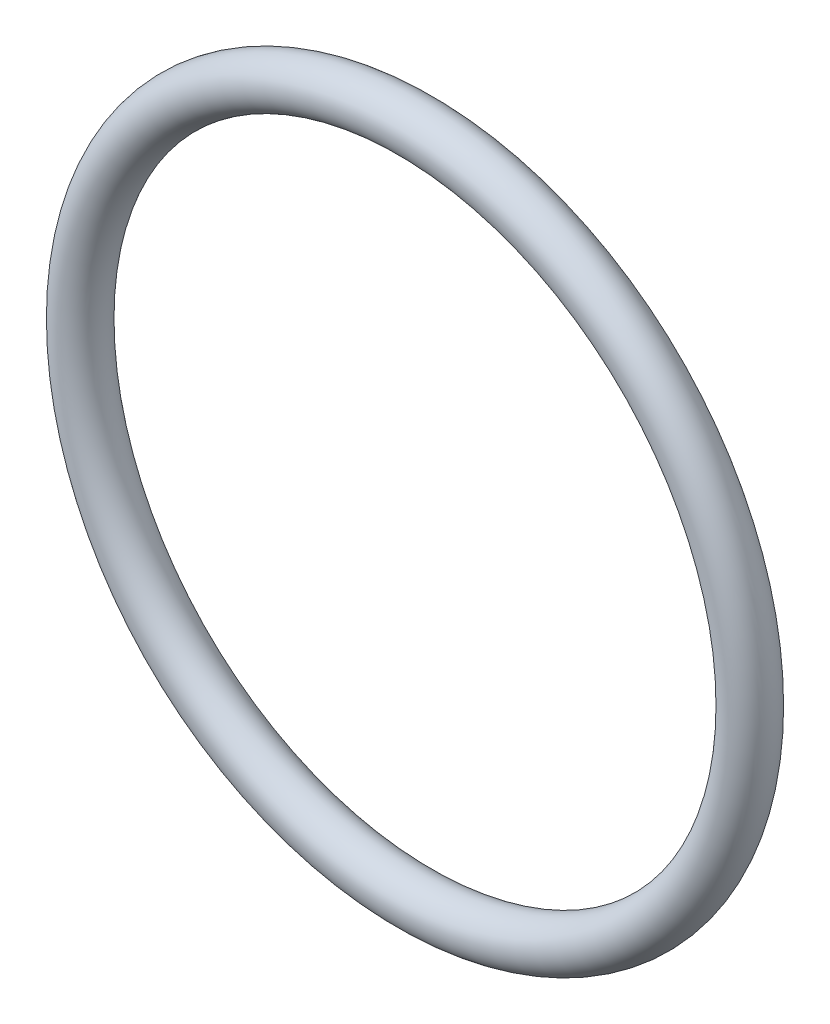
SolidWorks part; units mm, degrees
ref_plane "Front" through (0, 0, 0) normal (0, 0, 1) x (1, 0, 0)
ref_plane "Top" through (0, 0, 0) normal (0, 1, 0) x (1, 0, 0)
ref_plane "Right" through (0, 0, 0) normal (1, 0, 0) x (0, 0, -1)
sketch "Sketch1" plane through (0, 0, 0) normal (1, 0, 0) x (0, -1, 0)
  line L0 (0, -1.5) -> (0, 1.5) construction
  line L2 (-41.8, 0) -> (41.8, 0) construction
  line L3 (-19.5, 0) -> (19.5, 0) construction
  circle A0 centre (21, 0) radius 1.5
  point P9 (19.5, 0)
  point P10 (22.5, 0)
  point P13 (21, 1.5)
  point P14 (21, -1.5)
  dimension "Width" = 3
  dimension "ID" = 39
revolve "Revolve1" add sketch "Sketch1" angle 360 about L0
